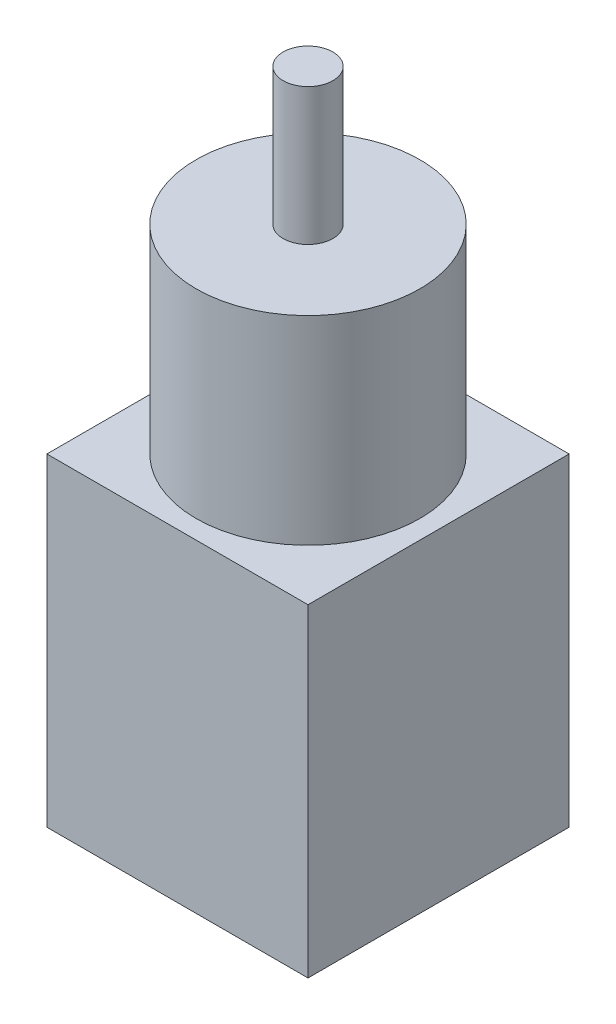
SolidWorks part; units mm, degrees
ref_plane "Front Plane" through (0, 0, 0) normal (0, 0, 1) x (1, 0, 0)
ref_plane "Top Plane" through (0, 0, 0) normal (0, 1, 0) x (1, 0, 0)
ref_plane "Right Plane" through (0, 0, 0) normal (1, 0, 0) x (0, 0, -1)
sketch "Sketch1" plane through (0, 0, 0) normal (0, 1, 0) x (1, 0, 0)
  line L1 (-21, -21) -> (21, -21)
  line L2 (-21, -21) -> (-21, 21)
  line L3 (-21, 21) -> (21, 21)
  line L4 (21, -21) -> (21, 21)
  line L5 (-21, -21) -> (21, 21) construction
  line L6 (-21, 21) -> (21, -21) construction
  point P0 (0, 0)
  dimension "D1" = 42
  dimension "D2" = 42
extrude "Boss-Extrude1" add sketch "Sketch1" along normal blind 52
sketch "Sketch2" plane through (0, 52, 0) normal (0, 1, 0) x (1, 0, 0)
  circle A0 centre (0, 0) radius 18
  dimension "D1" = 36
extrude "Boss-Extrude2" add sketch "Sketch2" along normal blind 32
sketch "Sketch3" plane through (0, 84, 0) normal (0, 1, 0) x (1, 0, 0)
  circle A0 centre (0, 0) radius 4
  dimension "D1" = 8
extrude "Boss-Extrude3" add sketch "Sketch3" along normal blind 22
sketch "Sketch4" plane through (0, 0, 0) normal (0, -1, 0) x (1, 0, 0)
  circle A0 centre (0, 0) radius 2.5
  dimension "D1" = 5
extrude "Boss-Extrude4" add sketch "Sketch4" along normal blind 11
